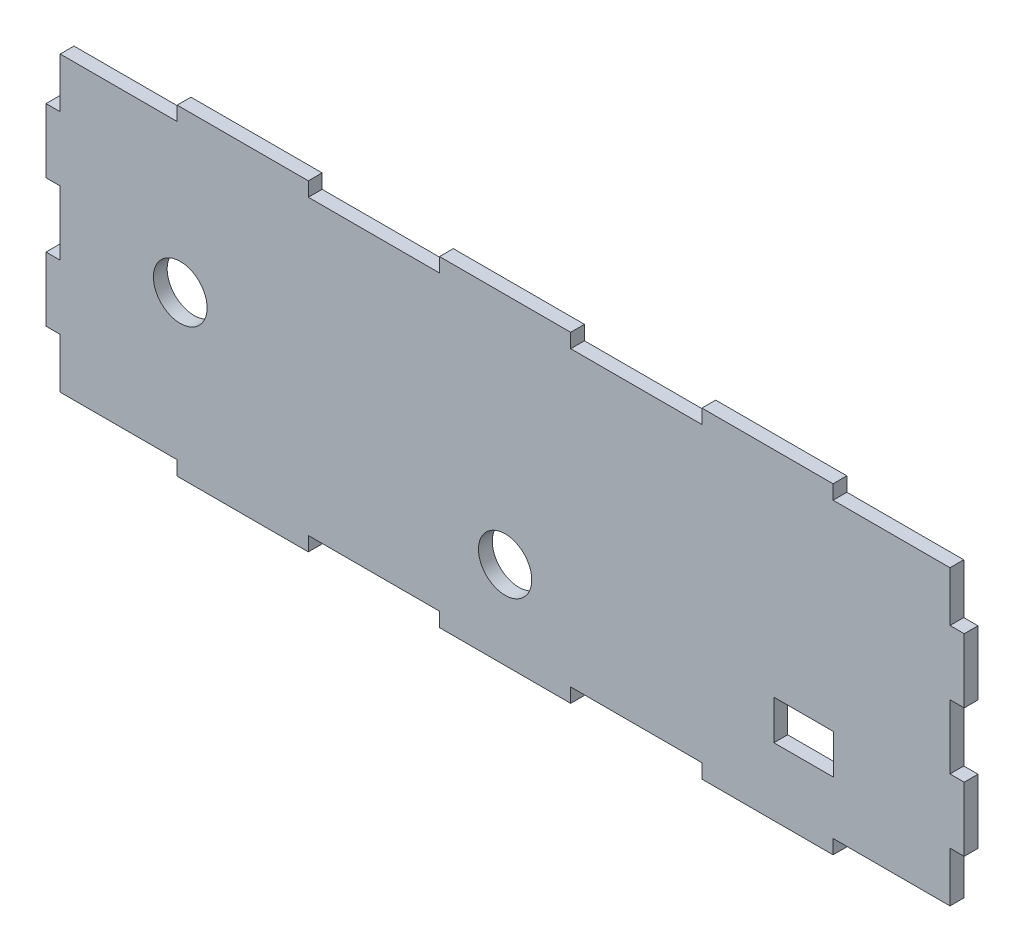
SolidWorks part; units mm, degrees
ref_plane "Alzado" through (0, 0, 0) normal (0, 0, 1) x (1, 0, 0)
ref_plane "Planta" through (0, 0, 0) normal (0, 1, 0) x (1, 0, 0)
ref_plane "Vista lateral" through (0, 0, 0) normal (1, 0, 0) x (0, 0, -1)
sketch "Croquis1" plane through (0, 0, 0) normal (0, 0, 1) x (1, 0, 0)
  line L0 (100, 0) -> (-100, 0) construction
  line L1 (-100, -35) -> (100, -35)
  line L2 (-100, -35) -> (-100, 35)
  line L3 (-100, 35) -> (100, 35)
  line L4 (100, -35) -> (100, 35)
  line L5 (-100, -35) -> (100, 35) construction
  line L6 (-100, 35) -> (100, -35) construction
  line L7 (-100, 35) -> (-71.4286, 35)
  line L8 (-100, 35) -> (-100, 31.9)
  line L9 (-100, 31.9) -> (-71.4286, 31.9)
  line L10 (-71.4286, 35) -> (-71.4286, 31.9)
  line L11 (-42.8571, 35) -> (-14.2857, 35)
  line L12 (-42.8571, 35) -> (-42.8571, 31.9)
  line L13 (-42.8571, 31.9) -> (-14.2857, 31.9)
  line L14 (-14.2857, 35) -> (-14.2857, 31.9)
  line L15 (14.2857, 35) -> (42.8571, 35)
  line L16 (14.2857, 35) -> (14.2857, 31.9)
  line L17 (14.2857, 31.9) -> (42.8571, 31.9)
  line L18 (42.8571, 35) -> (42.8571, 31.9)
  line L19 (71.4286, 35) -> (100, 35)
  line L20 (71.4286, 35) -> (71.4286, 31.9)
  line L21 (71.4286, 31.9) -> (100, 31.9)
  line L22 (100, 35) -> (100, 31.9)
  line L23 (0, 35) -> (0, -35) construction
  line L24 (-100, -35) -> (-96.9, -35)
  line L25 (-100, -35) -> (-100, -21)
  line L26 (-100, -21) -> (-96.9, -21)
  line L27 (-96.9, -35) -> (-96.9, -21)
  line L28 (-100, -7) -> (-96.9, -7)
  line L29 (-100, -7) -> (-100, 7)
  line L30 (-100, 7) -> (-96.9, 7)
  line L31 (-96.9, -7) -> (-96.9, 7)
  line L32 (-100, 21) -> (-96.9, 21)
  line L33 (-100, 21) -> (-100, 35)
  line L34 (-100, 35) -> (-96.9, 35)
  line L35 (-96.9, 21) -> (-96.9, 35)
  line L36 (100, -21) -> (96.9, -21)
  line L37 (96.9, -35) -> (96.9, -21)
  line L38 (100, -35) -> (96.9, -35)
  line L39 (100, -35) -> (100, -21)
  line L40 (100, 7) -> (96.9, 7)
  line L41 (96.9, -7) -> (96.9, 7)
  line L42 (100, -7) -> (96.9, -7)
  line L43 (100, -7) -> (100, 7)
  line L44 (100, 35) -> (96.9, 35)
  line L45 (96.9, 21) -> (96.9, 35)
  line L46 (100, 21) -> (96.9, 21)
  line L47 (100, 21) -> (100, 35)
  line L48 (71.4286, -31.9) -> (100, -31.9)
  line L49 (100, -35) -> (100, -31.9)
  line L50 (71.4286, -35) -> (100, -35)
  line L51 (71.4286, -35) -> (71.4286, -31.9)
  line L52 (14.2857, -31.9) -> (42.8571, -31.9)
  line L53 (42.8571, -35) -> (42.8571, -31.9)
  line L54 (14.2857, -35) -> (42.8571, -35)
  line L55 (14.2857, -35) -> (14.2857, -31.9)
  line L56 (-100, -31.9) -> (-71.4286, -31.9)
  line L57 (-71.4286, -35) -> (-71.4286, -31.9)
  line L58 (-100, -35) -> (-71.4286, -35)
  line L59 (-100, -35) -> (-100, -31.9)
  line L60 (-42.8571, -31.9) -> (-14.2857, -31.9)
  line L61 (-14.2857, -35) -> (-14.2857, -31.9)
  line L62 (-42.8571, -35) -> (-14.2857, -35)
  line L63 (-42.8571, -35) -> (-42.8571, -31.9)
  point P0 (0, 0)
  dimension "D2" = 70
  dimension "D3" = 28.5714
  dimension "D4" = 28.5714
  dimension "D5" = 28.5714
  dimension "D6" = 28.5714
  dimension "D7" = 28.5714
  dimension "D8" = 28.5714
  dimension "D9" = 28.5714
  dimension "D10" = 3.1
  dimension "D11" = 14
  dimension "D12" = 14
  dimension "D13" = 14
  dimension "D14" = 14
  dimension "D15" = 14
  dimension "D16" = 3.1
extrude "Saliente-Extruir2" add sketch "Croquis1" along normal blind 3 contours L4 L46 L45 L21 L20 L3 L18 L17 L16 L14 L13 L12 L10 L9 L35 L32 L2 L30 L31 L28 L26 L27 L1 L37 L36 L42 L41 L40
sketch "Croquis3" plane through (0, 0, 3) normal (0, 0, 1) x (1, 0, 0)
  circle A0 centre (-70.7551, 0) radius 5.85
extrude "Cortar-Extruir1" cut sketch "Croquis3" against normal blind 3
sketch "Croquis4" plane through (0, 0, 3) normal (0, 0, 1) x (1, 0, 0)
  line L1 (58.5363, -20.2959) -> (71.5363, -20.2959)
  line L2 (58.5363, -20.2959) -> (58.5363, -11.6959)
  line L3 (58.5363, -11.6959) -> (71.5363, -11.6959)
  line L4 (71.5363, -20.2959) -> (71.5363, -11.6959)
  dimension "D1" = 13
  dimension "D2" = 8.6
extrude "Cortar-Extruir2" cut sketch "Croquis4" against normal blind 3
sketch "Croquis5" plane through (0, 0, 0) normal (0, 0, -1) x (-1, 0, 0)
  circle A0 centre (0, -15.9507) radius 5.8
extrude "Cortar-Extruir3" cut sketch "Croquis5" against normal blind 3
